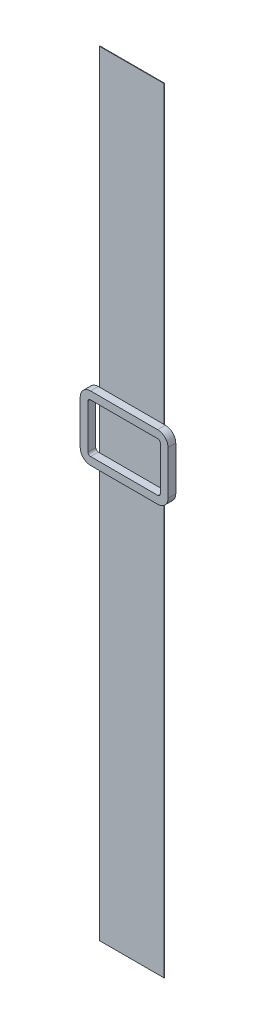
SolidWorks part; units mm, degrees
ref_plane "Plan de face" through (0, 0, 0) normal (0, 0, 1) x (1, 0, 0)
ref_plane "Plan de dessus" through (0, 0, 0) normal (0, 1, 0) x (1, 0, 0)
ref_plane "Plan de droite" through (0, 0, 0) normal (1, 0, 0) x (0, 0, -1)
sketch "Esquisse1" plane through (0, 0, 0) normal (0, 0, 1) x (1, 0, 0)
  line L1 (0, 0) -> (25, 0)
  line L2 (0, 0) -> (0, 300)
  line L3 (0, 300) -> (25, 300)
  line L4 (25, 0) -> (25, 300)
  dimension "D1" = 25
  dimension "D2" = 300
extrude "Extrusion1" add sketch "Esquisse1" along normal blind 0.2
sketch "Esquisse2" plane through (0, 0, 0.2) normal (0, 0, 1) x (1, 0, 0)
  line L0 (25, 300) -> (0, 300) construction
  line L1 (-0.5, 185.6529) -> (25.5, 185.6529)
  line L2 (-4.5, 181.6529) -> (-4.5, 164.6529)
  line L3 (-0.5, 160.6529) -> (25.5, 160.6529)
  line L4 (12.5, 300) -> (12.5, 321.3944) construction
  line L5 (-0.5, 182.6529) -> (25.5, 182.6529)
  line L6 (29.5, 181.6529) -> (29.5, 164.6529)
  line L7 (-0.5, 163.6529) -> (25.5, 163.6529)
  line L8 (-1.5, 181.6529) -> (-1.5, 164.6529)
  line L9 (24.6256, 181.6456) -> (24.5, 164.6456) construction
  line L10 (27.6255, 181.6234) -> (27.4999, 164.6234) construction
  line L11 (26.5, 181.6529) -> (26.5, 164.6529)
  line L12 (-0.5, 185.6529) -> (23.6256, 185.6529) construction
  line L13 (-0.5, 182.6529) -> (23.6256, 182.6529) construction
  line L14 (-0.5, 163.6529) -> (23.5, 163.6529) construction
  line L15 (-0.5, 160.6529) -> (23.5, 160.6529) construction
  arc A0 (-0.5, 185.6529) -> (-4.5, 181.6529) centre (-0.5, 181.6529) ccw
  arc A1 (-4.5, 164.6529) -> (-0.5, 160.6529) centre (-0.5, 164.6529) ccw
  arc A2 (29.5, 164.6529) -> (25.5, 160.6529) centre (25.5, 164.6529) cw
  arc A3 (26.5, 164.6529) -> (25.5, 163.6529) centre (25.5, 164.6529) cw
  arc A4 (25.5, 185.6529) -> (29.5, 181.6529) centre (25.5, 181.6529) cw
  arc A5 (25.5, 182.6529) -> (26.5, 181.6529) centre (25.5, 181.6529) cw
  arc A6 (-1.5, 164.6529) -> (-0.5, 163.6529) centre (-0.5, 164.6529) ccw
  arc A7 (-0.5, 182.6529) -> (-1.5, 181.6529) centre (-0.5, 181.6529) ccw
  arc A8 (23.6256, 182.6529) -> (24.6256, 181.6456) centre (23.6256, 181.6529) cw construction
  arc A9 (23.6256, 185.6529) -> (27.6255, 181.6234) centre (23.6256, 181.6529) cw construction
  arc A10 (23.5, 160.6529) -> (27.4999, 164.6234) centre (23.5, 164.6529) ccw construction
  arc A11 (23.5, 163.6529) -> (24.5, 164.6456) centre (23.5, 164.6529) ccw construction
  point P4 (12.5, 300)
  point P10 (-4.5, 185.6529)
  point P13 (-4.5, 160.6529)
  dimension "D4" = 4
  dimension "D1" = 17
  dimension "D3" = 25
  dimension "D5" = 3
extrude "Extrusion2" add sketch "Esquisse2" along normal blind 3
